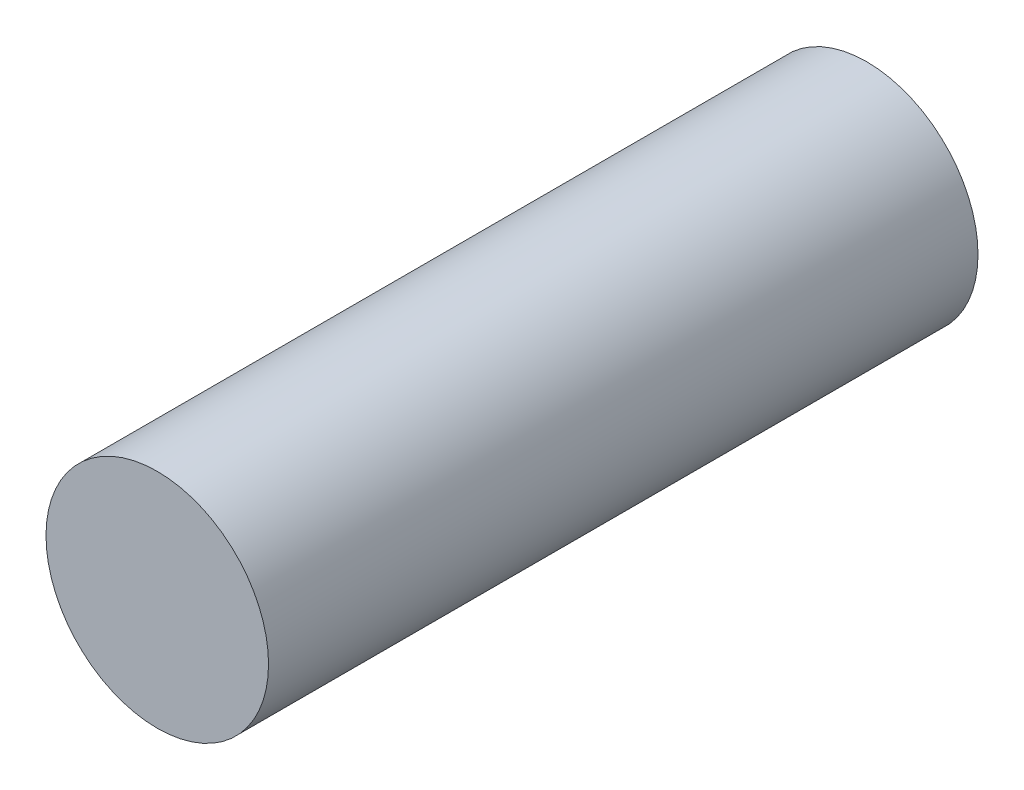
SolidWorks part; units mm, degrees
material "Plain Carbon Steel"
ref_plane "Front Plane" through (0, 0, 0) normal (0, 0, 1) x (1, 0, 0)
ref_plane "Top Plane" through (0, 0, 0) normal (0, 1, 0) x (1, 0, 0)
ref_plane "Right Plane" through (0, 0, 0) normal (1, 0, 0) x (0, 0, -1)
sketch "Sketch1" plane through (0, 0, 0) normal (0, 0, 1) x (1, 0, 0)
  circle A0 centre (0, 0) radius 9.755
  dimension "D1" = 19.51
extrude "Boss-Extrude1" add sketch "Sketch1" along normal blind 62.2
